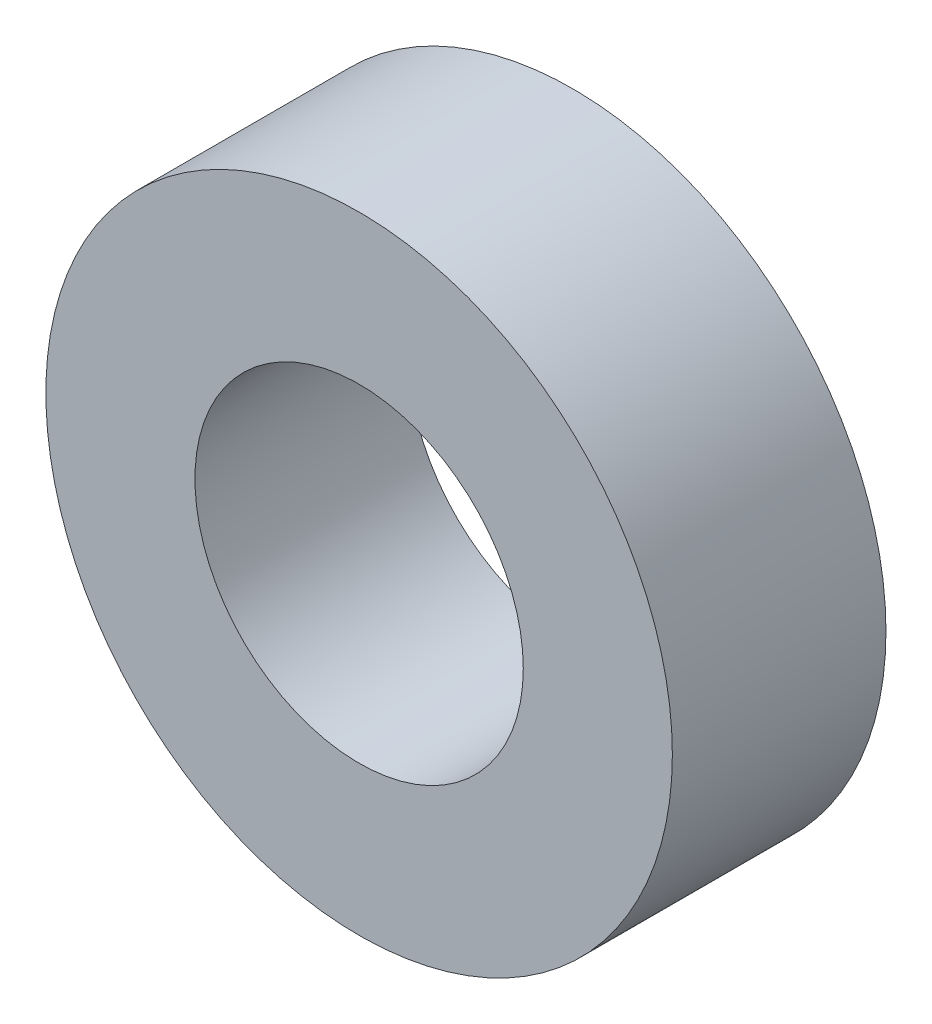
SolidWorks part; units mm, degrees
ref_plane "Plan de face" through (0, 0, 0) normal (1, 0, 0) x (0, 1, 0)
ref_plane "Plan de dessus" through (0, 0, 0) normal (0, 0, 1) x (0, 1, 0)
ref_plane "Plan de droite" through (0, 0, 0) normal (0, 1, 0) x (-1, 0, 0)
sketch "Esquisse1" plane through (0, 0, 0) normal (0, 0, 1) x (0, 1, 0)
  circle A0 centre (0, 0) radius 7.89
  circle A1 centre (0, 0) radius 4.135
  dimension "D1" = 8.27
  dimension "D2" = 15.78
extrude "Boss.-Extru.1" add sketch "Esquisse1" along normal blind 5.38
